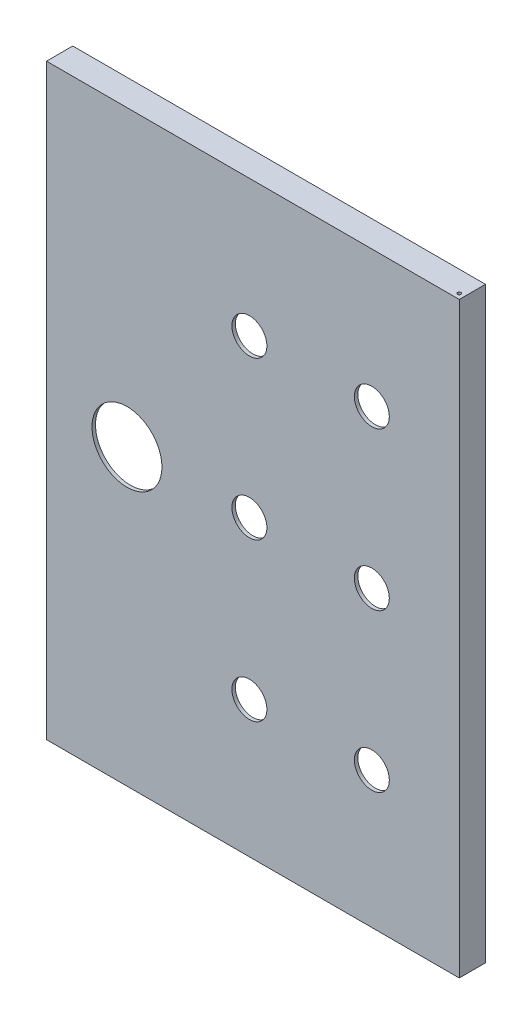
SolidWorks part; units mm, degrees
ref_plane "前视基准面" through (0, 0, 0) normal (0, 0, 1) x (1, 0, 0)
ref_plane "上视基准面" through (0, 0, 0) normal (0, 1, 0) x (1, 0, 0)
ref_plane "右视基准面" through (0, 0, 0) normal (1, 0, 0) x (0, 0, -1)
sketch "草图1" plane through (0, 0, 0) normal (0, 0, 1) x (1, 0, 0)
  line L0 (-118, -168) -> (-118, 168)
  line L1 (-118, -168) -> (118, -168)
  line L2 (-118, 168) -> (118, 168)
  line L3 (118, -168) -> (118, 168)
  line L4 (-118, -168) -> (118, 168) construction
  line L5 (-118, 168) -> (118, -168) construction
  point P1 (0, 0)
  dimension "D1" = 236
  dimension "D2" = 336
extrude "凸台-拉伸1" add sketch "草图1" along normal blind 15
shell "抽壳2" thickness 2
sketch "草图2" plane through (0, 0, 0) normal (0, 0, 1) x (1, 0, 0)
  line L0 (108, 158) -> (-108, 158)
  line L1 (-108, 158) -> (-108, -158)
  line L2 (-108, -158) -> (108, -158)
  line L3 (108, -158) -> (108, 158)
  line L4 (-116, 166) -> (-116, -166)
  line L5 (-116, -166) -> (116, -166)
  line L6 (116, -166) -> (116, 166)
  line L7 (116, 166) -> (-116, 166)
  line L8 (-116, 166) -> (-116, -166)
  line L9 (-116, -166) -> (116, -166)
  line L10 (116, -166) -> (116, 166)
  line L11 (116, 166) -> (-116, 166)
  dimension "D1" = 0
  dimension "D2" = 8
extrude "凸台-拉伸2" add sketch "草图2" along normal blind 2
sketch "草图3" plane through (0, 168, 0) normal (0, 1, 0) x (1, 0, 0)
  circle A0 centre (115, -12) radius 1
  dimension "D3" = 2
extrude "切除-拉伸1" cut sketch "草图3" against normal through all both and the other way through all
sketch "草图4" plane through (0, 0, 15) normal (0, 0, 1) x (1, 0, 0)
  line L0 (-118, 0) -> (192.3222, 0) construction
  line L1 (-118, 168) -> (-118, -168) construction
  circle A0 centre (-72, 0) radius 20
  circle A1 centre (-2, 0) radius 10
  circle A2 centre (68, 0) radius 10
  circle A3 centre (68, 90) radius 10
  circle A4 centre (-2, 90) radius 10
  circle A5 centre (68, -90) radius 10
  circle A6 centre (-2, -90) radius 10
  dimension "D4" = 40
  dimension "D7" = 20
  dimension "D8" = 20
extrude "切除-拉伸2" cut sketch "草图4" against normal blind 2
